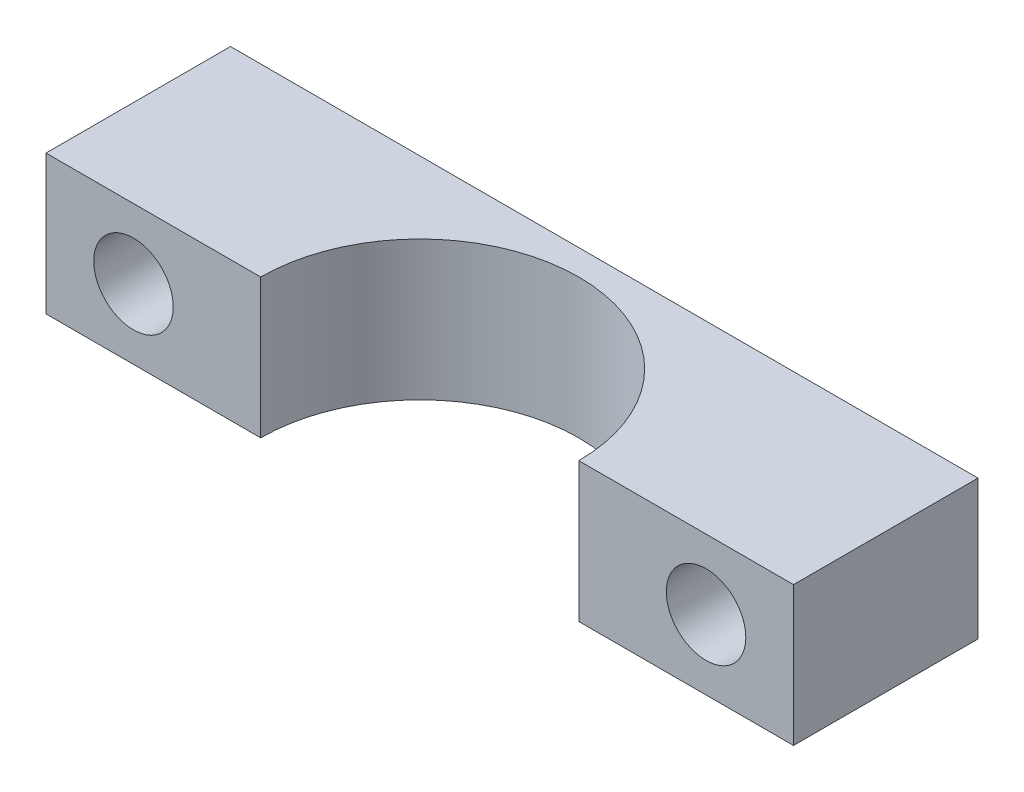
SolidWorks part; units mm, degrees
material "6061-T6 (SS)"
ref_plane "X-Y Datum" through (0, 0, 0) normal (0, 0, 1) x (1, 0, 0)
ref_plane "X-Z Datum" through (0, 0, 0) normal (0, 1, 0) x (1, 0, 0)
ref_plane "Y-Z Datum" through (0, 0, 0) normal (1, 0, 0) x (0, 0, -1)
sketch "Sketch1" plane through (0, 0, 0) normal (0, 1, 0) x (1, 0, 0)
  line L0 (-12.7, 0) -> (-29.845, 0)
  line L1 (-29.845, 0) -> (-29.845, 14.732)
  line L2 (-29.845, 14.732) -> (29.845, 14.732)
  line L3 (29.845, 14.732) -> (29.845, 0)
  line L4 (29.845, 0) -> (12.7, 0)
  line L10 (26.035, 0) -> (26.035, 14.732) construction
  line L11 (19.685, 0) -> (19.685, 14.732) construction
  line L12 (26.035, 7.366) -> (19.685, 7.366) construction
  arc A0 (-12.7, 0) -> (12.7, 0) centre (0, 0) cw
  point P16 (0, 0)
  point P17 (-17.7376, 0)
  point P18 (17.7376, 0)
  point P37 (22.86, 7.366)
  dimension "D1" = 14.732
  dimension "D2" = 12.7
  dimension "D9" = 6.35
  dimension "D3" = 59.69
  dimension "D6" = 22.86
extrude "Boss-Extrude1" add sketch "Sketch1" along normal mid plane 11.1252
sketch "Sketch2" plane through (0, 0, 0) normal (0, 0, 1) x (1, 0, 0)
  line L0 (-22.86, 0) -> (22.86, 0) construction
  circle A0 centre (-22.86, 0) radius 3.175
  circle A1 centre (22.86, 0) radius 3.175
  point P4 (0, 0)
  dimension "D1" = 6.35
  dimension "D2" = 22.86
extrude "Cut-Extrude1" cut sketch "Sketch2" against normal through all
fillet "Fillet1" [suppressed] radius 3.81
fillet "Fillet2" [suppressed] radius 0.254
